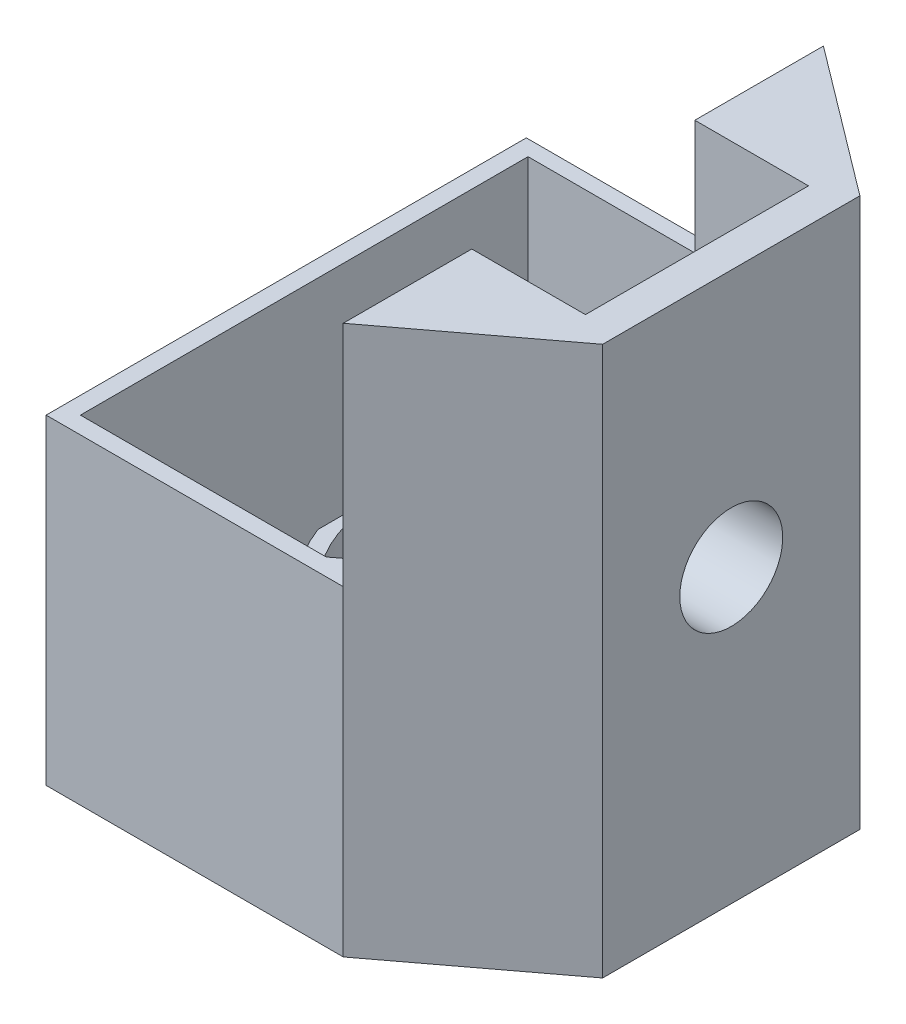
SolidWorks part; units mm, degrees
ref_plane "Front Plane" through (0, 0, 0) normal (0, 0, 1) x (1, 0, 0)
ref_plane "Top Plane" through (0, 0, 0) normal (0, 1, 0) x (1, 0, 0)
ref_plane "Right Plane" through (0, 0, 0) normal (1, 0, 0) x (0, 0, -1)
sketch "Sketch1" plane through (0, 0, 0) normal (1, 0, 0) x (0, 0, -1)
  line L1 (-10, 15) -> (10, 15)
  line L2 (-10, 15) -> (-10, -15)
  line L3 (-10, -15) -> (10, -15)
  line L4 (10, 15) -> (10, -15)
  point P4 (0, 15)
  point P6 (10, 0)
  dimension "D1" = 20
  dimension "D2" = 30
extrude "Boss-Extrude1" add sketch "Sketch1" along normal blind 2
sketch "Sketch2" plane through (0, 0, 0) normal (-1, 0, 0) x (0, 0, 1)
  circle A0 centre (0, 0) radius 3
  dimension "D1" = 6
extrude "Cut-Extrude1" cut sketch "Sketch2" against normal blind 2
sketch "Sketch4" plane through (0, 15, 0) normal (0, 1, 0) x (1, 0, 0)
  line L0 (5, 7.5) -> (-5.8089, 7.5) construction
  line L1 (5, -7.5) -> (-3.9815, -7.5) construction
  line L2 (2, 10) -> (2, -10) construction
  line L3 (0, 10) -> (2, 10)
  line L4 (0, 10) -> (0, 7.5)
  line L5 (0, 7.5) -> (2, 7.5)
  line L6 (2, 10) -> (2, 7.5)
  line L8 (0, -10) -> (2, -10)
  line L9 (0, -10) -> (0, -7.5)
  line L10 (0, -7.5) -> (2, -7.5)
  line L11 (2, -10) -> (2, -7.5)
extrude "Cut-Extrude2" cut sketch "Sketch4" against normal through all
sketch "Sketch5" plane through (0, 15, 0) normal (0, 1, 0) x (1, 0, 0)
  line L0 (5, 7.5) -> (-19.8169, 7.5) construction
  line L1 (5, -7.5) -> (-19.8169, -7.5) construction
  line L2 (5, 7.5) -> (16.6472, 16.2338) construction
  line L3 (16.6472, 14) -> (-45.3379, 14) construction
  line L4 (24.6667, 14) -> (13.6667, 14) construction
  line L5 (5, -7.5) -> (16.6472, -16.2122) construction
  line L6 (16.6472, -14) -> (-45.3379, -14) construction
  line L7 (13.6667, -14) -> (24.6667, -14) construction
  line L8 (2, 7.5) -> (-6.6258, 14)
  line L9 (0, 6.5028) -> (-9.9491, 14)
  line L10 (0, 7.5) -> (0, -7.5) construction
  line L11 (-6.6258, 14) -> (-9.9491, 14)
  line L12 (0, 0) -> (-18.2908, 0) construction
  line L13 (0, 6.5028) -> (2, 7.5)
  line L14 (-6.6258, -14) -> (-9.9491, -14)
  line L15 (0, -6.5028) -> (-9.9491, -14)
  line L16 (2, -7.5) -> (-6.6258, -14)
  line L17 (0, -6.5028) -> (2, -7.5)
  dimension "D1" = 37
  dimension "D2" = 2
extrude "Boss-Extrude2" add sketch "Sketch5" against normal through all
sketch "Sketch6" plane through (0, 0, 0) normal (-1, 0, 0) x (0, 0, 1)
  circle A0 centre (0, 0) radius 3
  circle A1 centre (0, 0) radius 5
  dimension "D1" = 6
  dimension "D2" = 2
extrude "Boss-Extrude3" add sketch "Sketch6" along normal blind 3
sketch "Sketch7" plane through (0, -15, 0) normal (0, -1, 0) x (1, 0, 0)
  line L0 (-6.6258, -14) -> (-9.9491, -14) construction
  line L1 (-9.9491, 14) -> (-6.6258, 14)
  line L2 (-9.9491, 14) -> (-9.9491, -14)
  line L3 (-9.9491, -14) -> (-6.6258, -14)
  line L4 (2, 7.5) -> (2, -7.5)
  line L5 (-6.6258, -14) -> (2, -7.5)
  line L6 (-6.6258, 14) -> (2, 7.5)
extrude "Boss-Extrude4" add sketch "Sketch7" along normal blind 2
sketch "Sketch8" plane through (0, -17, 0) normal (0, -1, 0) x (1, 0, 0)
  line L0 (-6.6258, 14) -> (-9.9491, 14) construction
  line L1 (-9.9491, -14) -> (-23.9491, -14)
  line L2 (-9.9491, -14) -> (-9.9491, 14)
  line L3 (-9.9491, 14) -> (-23.9491, 14)
  line L4 (-23.9491, -14) -> (-23.9491, 14)
  dimension "D1" = 14
extrude "Boss-Extrude5" add sketch "Sketch8" against normal blind 2
sketch "Sketch9" plane through (0, -15, 0) normal (0, 1, 0) x (1, 0, 0)
  circle A0 centre (-13.8841, 4.2795) radius 8.8106
  circle A1 centre (-13.8841, 4.2795) radius 9.6913
extrude "Boss-Extrude6" add sketch "Sketch9" along normal blind 4
sketch "Sketch10" plane through (0, -15, 0) normal (0, 1, 0) x (1, 0, 0)
  line L0 (-6.6258, -14) -> (-6.6258, -13)
  line L1 (-23.9491, -14) -> (-6.6258, -14)
  line L2 (-23.9491, -14) -> (-23.9491, 14)
  line L3 (-23.9491, 14) -> (-6.6258, 14)
  line L5 (-22.9491, -13) -> (-7.7546, -13)
  line L6 (-22.9491, -13) -> (-22.9491, 13.1)
  line L7 (-22.9491, 13.1) -> (-7.7546, 13.1)
  line L9 (-6.6258, -13) -> (-7.7546, -13)
  line L10 (-6.6258, 14) -> (-6.6258, 13.1)
  line L11 (-6.6258, 13.1) -> (-7.7546, 13.1)
  dimension "D1" = 0.9
  dimension "D2" = 1
  dimension "D3" = 1
extrude "Boss-Extrude7" add sketch "Sketch10" along normal up to surface (30 mm away) up to face at (-3.6437, 15, 0)
sketch "Sketch11" plane through (0, 0, -14) normal (0, 0, -1) x (-1, 0, 0)
  line L0 (16.9341, 1.7) -> (23.9491, 1.7)
  line L1 (16.9341, 0.9) -> (16.9341, 2.5) construction
  line L2 (23.9491, 15) -> (23.9491, -17) construction
  line L3 (16.9341, 1.7) -> (6.6258, 1.7)
  line L4 (6.6258, -17) -> (6.6258, 15) construction
  line L6 (6.6258, 15) -> (23.9491, 15)
  line L7 (23.9491, 15) -> (23.9491, 1.7)
  line L13 (6.6258, 15) -> (6.6258, 1.7)
extrude "Cut-Extrude3" cut sketch "Sketch11" against normal through all
sketch "Sketch13" plane through (0, 1.7, 0) normal (0, 1, 0) x (1, 0, 0)
  line L2 (-6.6258, -14) -> (-6.6258, -6.5028)
  line L5 (-6.6258, -14) -> (0, -9.0071)
  line L6 (0, 9.0071) -> (-6.6258, 14)
  line L7 (0, -6.5028) -> (-6.6258, -6.5028)
  line L8 (0, 6.5028) -> (-6.6258, 6.5028)
  line L9 (0, -6.5028) -> (0, -9.0071)
  line L10 (0, 6.5028) -> (0, 9.0071)
  line L11 (-6.6258, 6.5028) -> (-6.6258, 14)
extrude "Boss-Extrude8" add sketch "Sketch13" along normal up to surface (13.3 mm away) up to face at (-2.8129, 15, 0)
sketch "Sketch17" plane through (0, -17, 0) normal (0, -1, 0) x (1, 0, 0)
  line L0 (-6.6258, 14) -> (-23.9491, 14) construction
  line L1 (-19.9491, 12) -> (-9.9491, 12)
  line L2 (-19.9491, 12) -> (-19.9491, 7)
  line L3 (-19.9491, 7) -> (-9.9491, 7)
  line L4 (-9.9491, 12) -> (-9.9491, 7)
  line L5 (-23.9491, 14) -> (-23.9491, -14) construction
  dimension "D1" = 10
  dimension "D2" = 5
  dimension "D3" = 2
  dimension "D4" = 4
extrude "Cut-Extrude5" cut sketch "Sketch17" against normal blind 2
